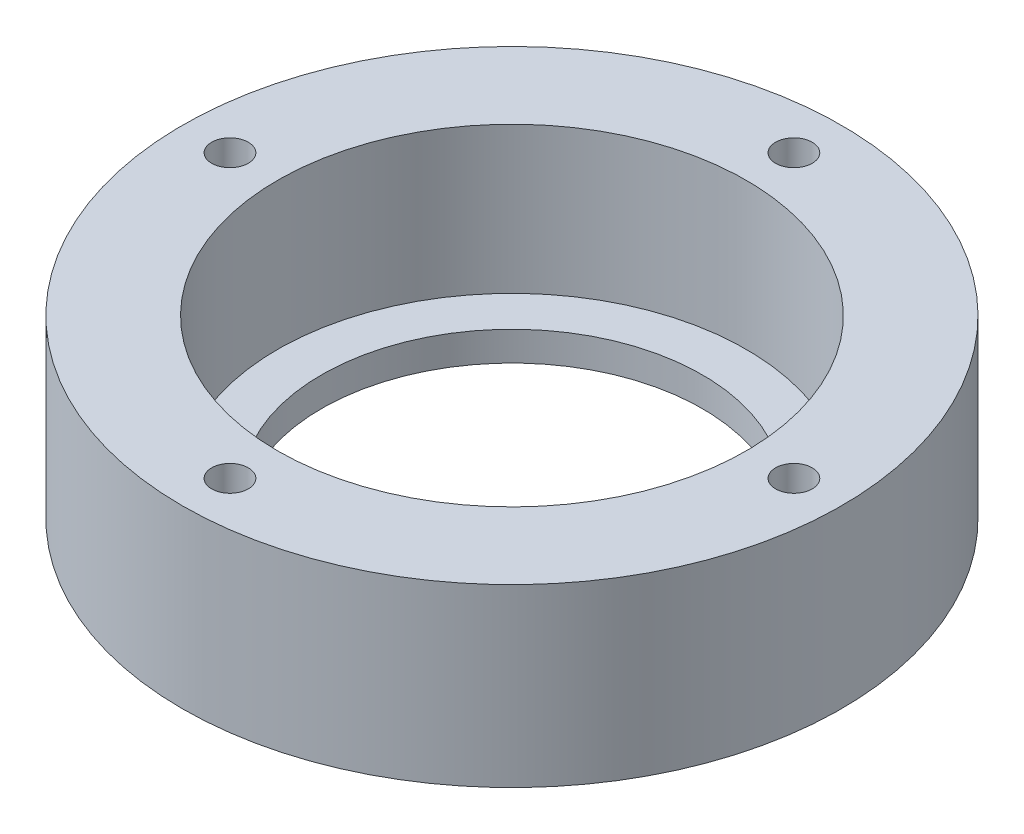
SolidWorks part; units mm, degrees
ref_plane "Спереди" through (0, 0, 0) normal (0, 0, 1) x (1, 0, 0)
ref_plane "Сверху" through (0, 0, 0) normal (0, 1, 0) x (1, 0, 0)
ref_plane "Справа" through (0, 0, 0) normal (1, 0, 0) x (0, 0, -1)
sketch "Эскиз1" plane through (0, 0, 0) normal (0, 1, 0) x (1, 0, 0)
  circle A0 centre (0, 0) radius 22.5
  dimension "D1" = 45
extrude "Бобышка-Вытянуть1" add sketch "Эскиз1" along normal blind 12
sketch "Эскиз2" plane through (0, 12, 0) normal (0, 1, 0) x (1, 0, 0)
  circle A0 centre (0, 0) radius 16
  dimension "D1" = 32
extrude "Вырез-Вытянуть1" cut sketch "Эскиз2" against normal blind 10
sketch "Эскиз3" plane through (0, 2, 0) normal (0, 1, 0) x (1, 0, 0)
  circle A0 centre (0, 0) radius 13
  dimension "D1" = 26
extrude "Вырез-Вытянуть2" cut sketch "Эскиз3" against normal through all
sketch "Эскиз4" plane through (0, 12, 0) normal (0, 1, 0) x (1, 0, 0)
  line L0 (0, 25.6262) -> (0, -25.6262) construction
  line L1 (-26.9212, 0) -> (26.9212, 0) construction
  circle A0 centre (0, 0) radius 19.25 construction
  dimension "D1" = 38.5
hole_wizard "Отверстие обработанное метчиком M3x0.51" positions "Эскиз6" profile "Эскиз5" tap size "M3x0.5" standard "Ansi Metric"
sketch "Эскиз6" plane through (0, 12, 0) normal (0, 1, 0) x (1, 0, 0)
  line L0 (-26.9212, 0) -> (26.9212, 0) construction
  line L1 (0, 25.6262) -> (0, -25.6262) construction
  circle A0 centre (0, 0) radius 19.25 construction
  point P0 (-19.25, 0)
  point P6 (0, -19.25)
  point P10 (19.25, 0)
  point P12 (0, 19.25)
sketch "Эскиз5" plane through (-19.25, 12, 0) normal (1, 0, 0) x (0, 0, 1)
  line L0 (0, 0) -> (0, 9.2511)
  line L1 (0, 9.2511) -> (1.25, 8.5)
  line L2 (1.25, 8.5) -> (1.25, 0)
  line L5 (1.25, 0) -> (0, 0)
  line L10 (0, 9.2511) -> (-1.25, 8.5) construction
  line L11 (0, -6.35) -> (0, 107.95) construction
  dimension "Диаметр сверла" = 2.5
  dimension "Глубина сверла" = 8.5
  dimension "Угол заточки сверла" = 118
